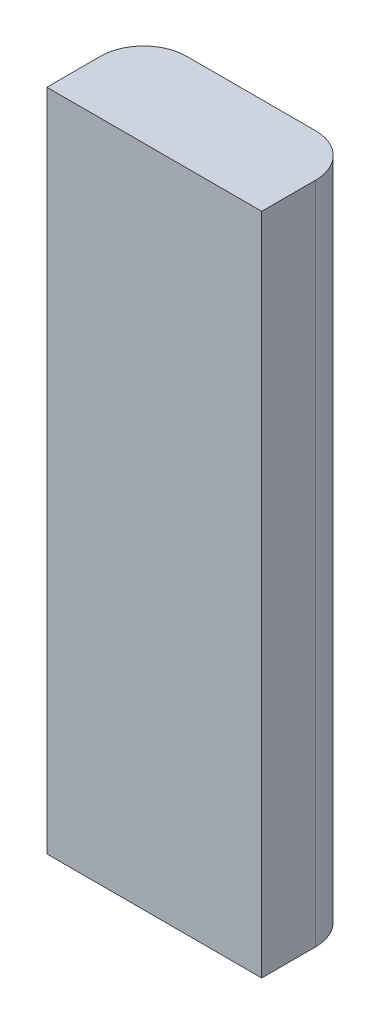
SolidWorks part; units mm, degrees
ref_plane "Front Plane" through (0, 0, 0) normal (0, 0, 1) x (1, 0, 0)
ref_plane "Top Plane" through (0, 0, 0) normal (0, 1, 0) x (1, 0, 0)
ref_plane "Right Plane" through (0, 0, 0) normal (1, 0, 0) x (0, 0, -1)
sketch "Sketch1" plane through (0, 0, 0) normal (0, 1, 0) x (1, 0, 0)
  line L1 (0, 0) -> (127, 0)
  line L2 (0, 0) -> (0, 31.75)
  line L3 (25.4, 57.15) -> (101.6, 57.15)
  line L4 (127, 0) -> (127, 31.75)
  arc A0 (101.6, 57.15) -> (127, 31.75) centre (101.6, 31.75) cw
  arc A1 (0, 31.75) -> (25.4, 57.15) centre (25.4, 31.75) cw
  point P7 (127, 57.15)
  point P10 (0, 57.15)
  dimension "D3" = 25.4
  dimension "D1" = 127
  dimension "D2" = 57.15
extrude "Boss-Extrude1" add sketch "Sketch1" along normal blind 392.43
